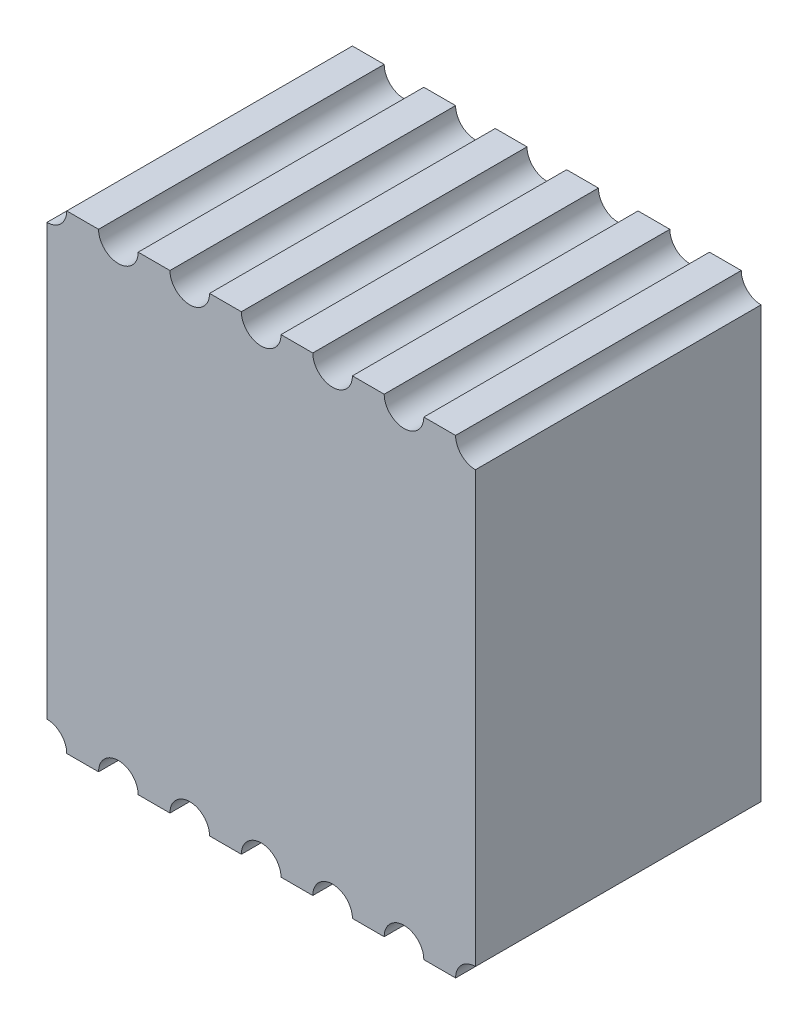
SolidWorks part; units mm, degrees
ref_plane "Front Plane" through (0, 0, 0) normal (0, 0, 1) x (1, 0, 0)
ref_plane "Top Plane" through (0, 0, 0) normal (0, 1, 0) x (1, 0, 0)
ref_plane "Right Plane" through (0, 0, 0) normal (1, 0, 0) x (0, 0, -1)
sketch "Sketch1" plane through (0, 0, 0) normal (0, 0, 1) x (1, 0, 0)
  line L38 (11.445, 13.16) -> (10.555, 13.16)
  line L40 (9.445, 13.16) -> (8.555, 13.16)
  line L44 (7.445, 13.16) -> (6.555, 13.16)
  line L53 (5.445, 13.16) -> (4.555, 13.16)
  line L54 (3.445, 13.16) -> (2.555, 13.16)
  line L55 (1.445, 13.16) -> (0.555, 13.16)
  line L56 (1.445, 0) -> (0.555, 0)
  line L57 (3.445, 0) -> (2.555, 0)
  line L58 (5.445, 0) -> (4.555, 0)
  line L59 (7.445, 0) -> (6.555, 0)
  line L60 (9.445, 0) -> (8.555, 0)
  line L61 (11.445, 0) -> (10.555, 0)
  line L62 (0, 12.605) -> (0, 0.555)
  line L63 (12, 12.605) -> (12, 0.555)
  arc A46 (9.445, 13.16) -> (10.555, 13.16) centre (10, 13.16) ccw
  arc A47 (11.445, 13.16) -> (12, 12.605) centre (12, 13.16) ccw
  arc A48 (7.445, 13.16) -> (8.555, 13.16) centre (8, 13.16) ccw
  arc A49 (6.555, 13.16) -> (5.445, 13.16) centre (6, 13.16) cw
  arc A50 (4.555, 13.16) -> (3.445, 13.16) centre (4, 13.16) cw
  arc A51 (1.445, 13.16) -> (2.555, 13.16) centre (2, 13.16) ccw
  arc A52 (0.555, 13.16) -> (0, 12.605) centre (0, 13.16) cw
  arc A53 (0.555, 0) -> (0, 0.555) centre (0, 0) ccw
  arc A54 (1.445, 0) -> (2.555, 0) centre (2, 0) cw
  arc A55 (4.555, 0) -> (3.445, 0) centre (4, 0) ccw
  arc A56 (6.555, 0) -> (5.445, 0) centre (6, 0) ccw
  arc A57 (7.445, 0) -> (8.555, 0) centre (8, 0) cw
  arc A58 (11.445, 0) -> (12, 0.555) centre (12, 0) cw
  arc A59 (9.445, 0) -> (10.555, 0) centre (10, 0) cw
extrude "Boss-Extrude1" add sketch "Sketch1" along normal blind 8
